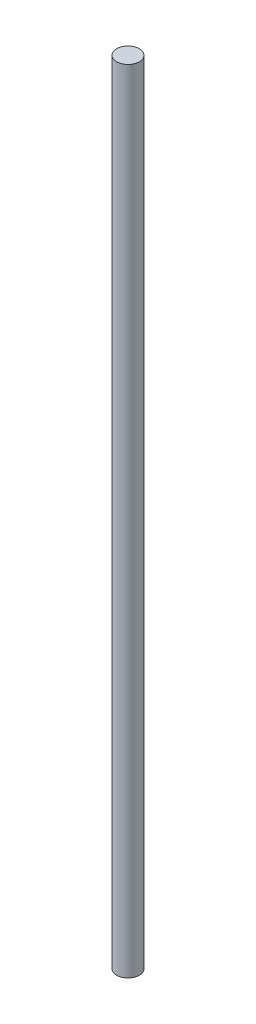
SolidWorks part; units mm, degrees
material "镀铬不锈钢"
ref_plane "前视基准面" through (0, 0, 0) normal (0, 0, 1) x (1, 0, 0)
ref_plane "上视基准面" through (0, 0, 0) normal (0, 1, 0) x (1, 0, 0)
ref_plane "右视基准面" through (0, 0, 0) normal (1, 0, 0) x (0, 0, -1)
sketch "草图1" plane through (0, 0, 0) normal (0, 1, 0) x (1, 0, 0)
  circle A0 centre (0, 0) radius 0.5
  dimension "D1" = 1
extrude "凸台-拉伸1" add sketch "草图1" along normal blind 35
